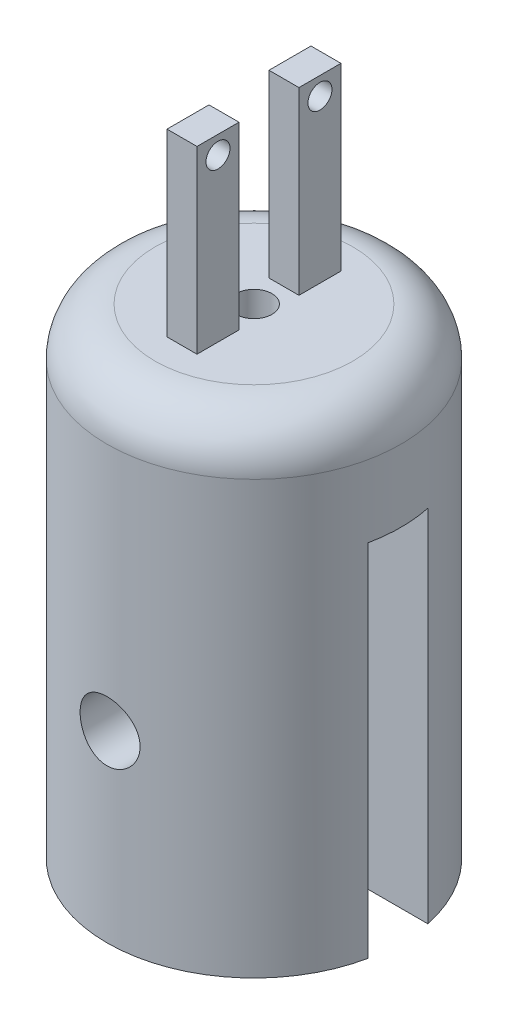
SolidWorks part; units mm, degrees
ref_plane "Front Plane" through (0, 0, 0) normal (0, 0, 1) x (1, 0, 0)
ref_plane "Top Plane" through (0, 0, 0) normal (0, 1, 0) x (1, 0, 0)
ref_plane "Right Plane" through (0, 0, 0) normal (1, 0, 0) x (0, 0, -1)
sketch "Sketch1" plane through (0, 0, 0) normal (0, 1, 0) x (1, 0, 0)
  circle A0 centre (0, 0) radius 24.5
  dimension "D1" = 49
extrude "Boss-Extrude1" add sketch "Sketch1" along normal blind 80
fillet "Fillet1" radius 8 1 edges at (0, 80, 24.5)
sketch "Sketch2" plane through (0, 0, 0) normal (0, 0, 1) x (1, 0, 0)
  circle A0 centre (0, 30.57) radius 5
  dimension "D1" = 10
  dimension "D2" = 30.57
extrude "Cut-Extrude1" cut sketch "Sketch2" against normal through all and the other way through all
sketch "Sketch3" plane through (0, 0, 0) normal (0, 1, 0) x (1, 0, 0)
  line L1 (26.6564, 5) -> (-29.3754, 5)
  line L2 (26.6564, 5) -> (26.6564, -5)
  line L3 (26.6564, -5) -> (-29.3754, -5)
  line L4 (-29.3754, 5) -> (-29.3754, -5)
  point P6 (-2.9451, -15.2894)
  dimension "D1" = 10
  dimension "D2" = 5
extrude "Cut-Extrude2" cut sketch "Sketch3" along normal blind 60
sketch "Sketch4" plane through (0, 80, 0) normal (0, 1, 0) x (1, 0, 0)
  circle A0 centre (0, 0) radius 3
  dimension "D1" = 6
extrude "Cut-Extrude3" cut sketch "Sketch4" against normal blind 60
sketch "Sketch5" plane through (0, 80, 0) normal (0, 1, 0) x (1, 0, 0)
  line L1 (-2.5, 5) -> (2.5, 5)
  line L2 (-2.5, 5) -> (-2.5, 12)
  line L3 (-2.5, 12) -> (2.5, 12)
  line L4 (2.5, 5) -> (2.5, 12)
  point P4 (0, 0)
  point P5 (0, 5)
  dimension "D1" = 7
  dimension "D2" = 5
  dimension "D3" = 5
extrude "Boss-Extrude2" add sketch "Sketch5" along normal blind 30
sketch "Sketch6" plane through (-2.5, 0, 0) normal (-1, 0, 0) x (0, 0, 1)
  line L0 (-12, 110) -> (-5, 110) construction
  circle A0 centre (-8.5, 107) radius 2
  dimension "D1" = 4
  dimension "D2" = 3
extrude "Cut-Extrude4" cut sketch "Sketch6" against normal through all contours A0
mirror "Mirror1" about plane through (0, 0, 0) normal (0, 0, 1) of "Cut-Extrude4", "Boss-Extrude2"
